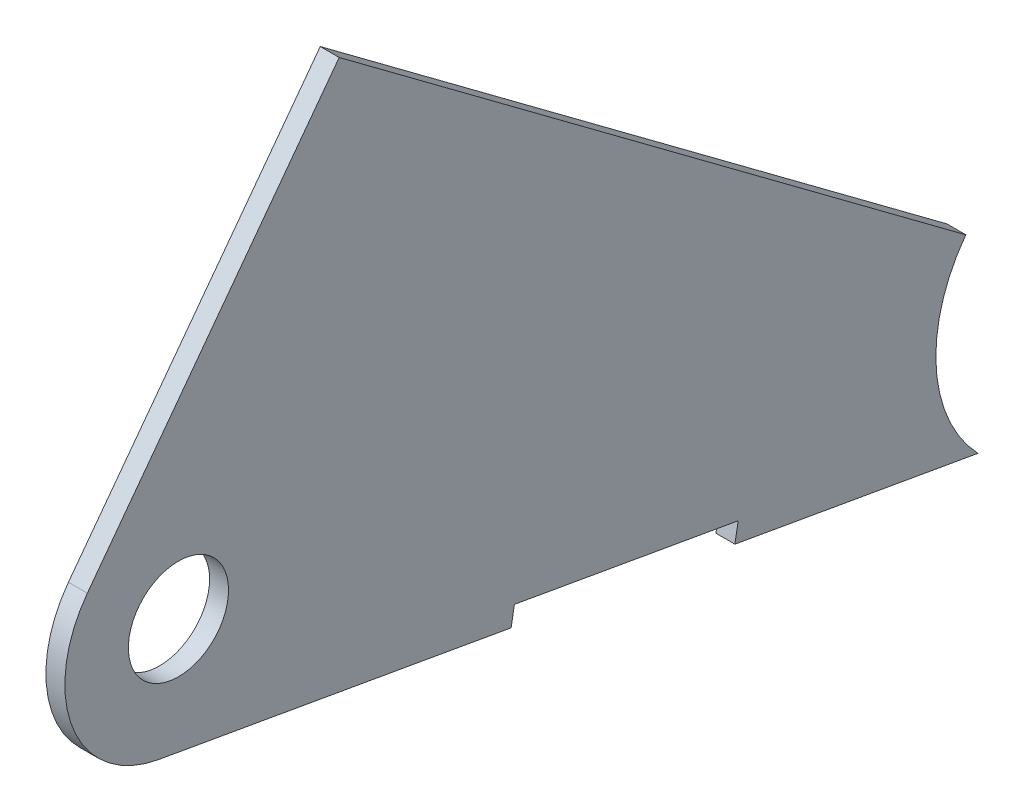
SolidWorks part; units mm, degrees
material "AISI 4130 Steel, annealed at 865C"
ref_plane "X-Y Datum" through (0, 0, 0) normal (0, 0, 1) x (1, 0, 0)
ref_plane "X-Z Datum" through (0, 0, 0) normal (0, 1, 0) x (1, 0, 0)
ref_plane "Y-Z Datum" through (0, 0, 0) normal (1, 0, 0) x (0, 0, -1)
sketch "Sketch1" plane through (0, 0, 0) normal (1, 0, 0) x (0, 0, -1)
  line L0 (-7.6382, 5.6907) -> (13.4764, 34.0312)
  line L1 (13.4764, 34.0312) -> (76.2, -12.7)
  line L2 (76.2, -12.7) -> (76.2, -23.1081)
  line L3 (76.2, -23.1081) -> (-1.654, -9.3803)
  line L4 (-50.469, 81.6727) -> (76.2, -12.7) construction
  line L5 (76.2, 25.4) -> (76.2, -431.8) construction
  line L6 (0.0738, 16.0418) -> (5.7645, 23.68)
  line L7 (0.0738, 16.0418) -> (1.3468, 15.0934)
  line L8 (5.7645, 23.68) -> (7.0375, 22.7316)
  line L9 (1.3468, 15.0934) -> (7.0375, 22.7316)
  line L10 (27.8927, -14.5902) -> (46.6533, -17.8982)
  line L11 (27.8927, -14.5902) -> (28.1684, -13.0268)
  line L12 (46.6533, -17.8982) -> (46.929, -16.3348)
  line L13 (28.1684, -13.0268) -> (46.929, -16.3348)
  arc A0 (-7.6382, 5.6907) -> (-1.654, -9.3803) centre (0, 0) ccw
  circle A1 centre (76.2, -12.7) radius 12.7
  point P11 (2.9191, 19.8609)
  point P14 (2.9191, 19.8609)
  point P17 (37.273, -16.2442)
  point P18 (37.273, -16.2442)
  dimension "D1" = 9.525
  dimension "D6" = 25.4
  dimension "D2" = 80
  dimension "D3" = 1.5875
  dimension "D4" = 9.525
  dimension "D5" = 19.05
extrude "Boss-Extrude1" add sketch "Sketch1" along normal blind 1.5875 contours L0 A0 L3 L11 L13 L12 L2 L1 L8 L9 L7 | L7 L9 L8 L0
hole_wizard "M8 Clearance Hole1" positions "Sketch2" profile "Sketch3" hole size "M8" standard "ANSI Metric" end condition through all
sketch "Sketch2" plane through (1.5875, 0, 0) normal (1, 0, 0) x (0, 0, -1)
  point P0 (0, 0)
sketch "Sketch3" plane through (1.5875, 0, 0) normal (0, 1, 0) x (0, 0, -1)
  line L0 (0, 0) -> (0, 1.5875)
  line L1 (0, 1.5875) -> (4.2, 1.5875)
  line L2 (4.2, 1.5875) -> (4.2, 0)
  line L5 (4.2, 0) -> (0, 0)
  line L11 (0, -6.35) -> (0, 107.95) construction
  dimension "Thru Hole Dia." = 8.4
  dimension "Thru Hole Depth" = 1.5875
